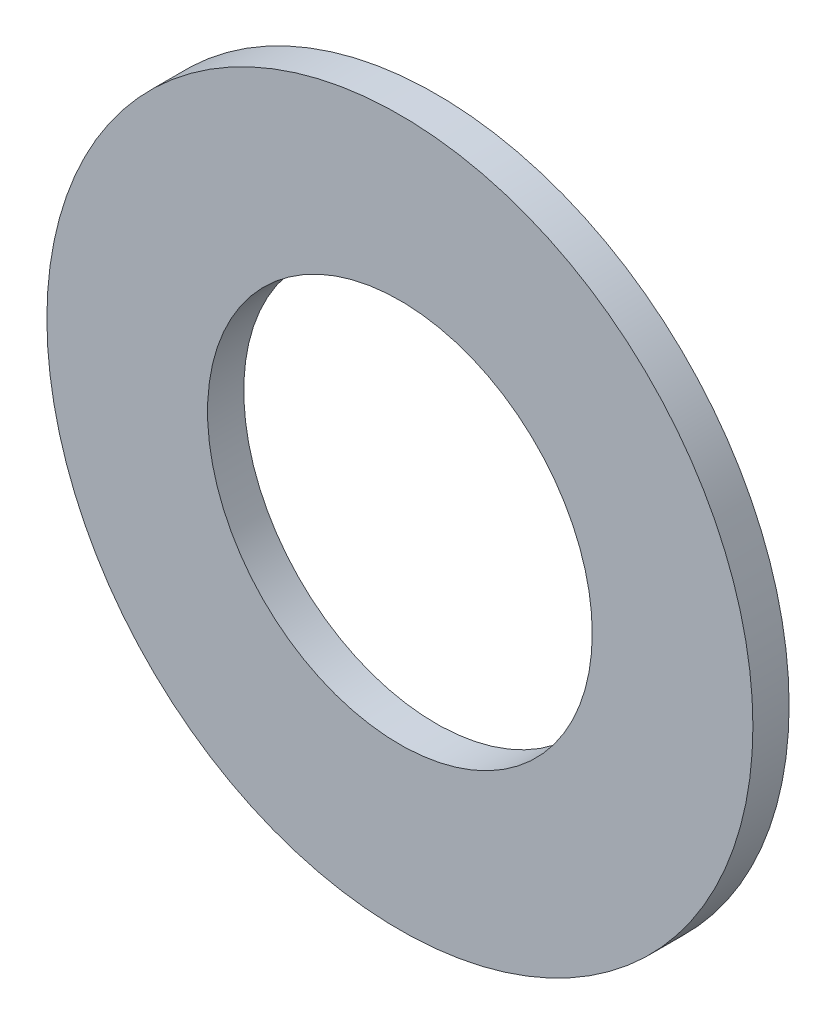
SolidWorks part; units mm, degrees
ref_plane "Front Plane" through (0, 0, 0) normal (0, 0, 1) x (1, 0, 0)
ref_plane "Top Plane" through (0, 0, 0) normal (0, 1, 0) x (1, 0, 0)
ref_plane "Right Plane" through (0, 0, 0) normal (1, 0, 0) x (0, 0, -1)
sketch "Sketch3" plane through (0, 0, 0) normal (0, 0, 1) x (1, 0, 0)
  circle A0 centre (0, 0) radius 78
  circle A1 centre (0, 0) radius 42.5
  dimension "D1" = 156
  dimension "D2" = 85
extrude "Boss-Extrude1" add sketch "Sketch3" along normal blind 8
